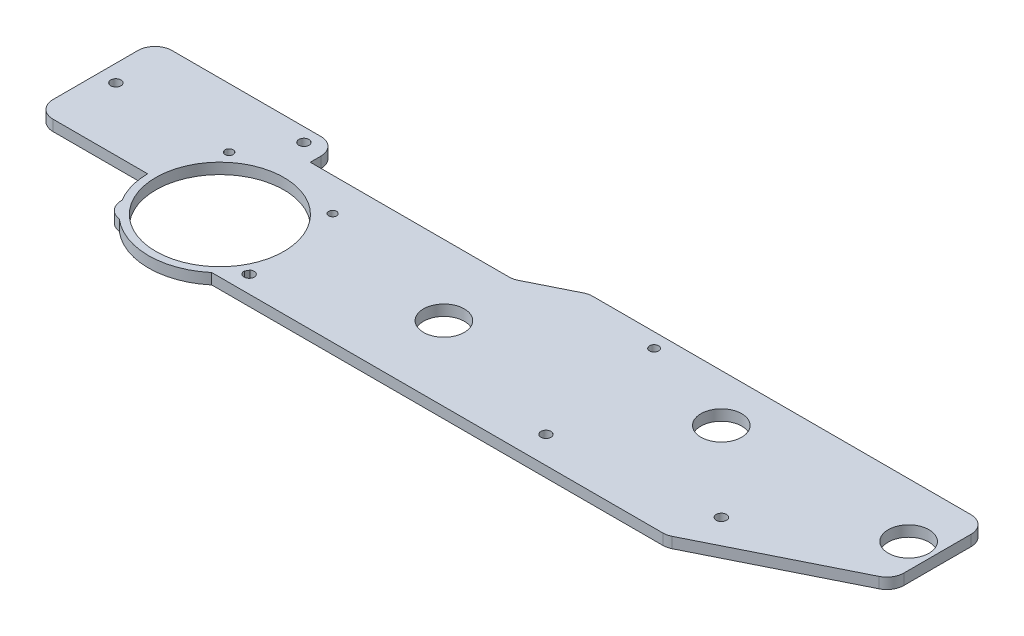
SolidWorks part; units mm, degrees
ref_plane "Front" through (0, 0, 0) normal (0, 0, 1) x (1, 0, 0)
ref_plane "Top" through (0, 0, 0) normal (0, 1, 0) x (1, 0, 0)
ref_plane "Right" through (0, 0, 0) normal (1, 0, 0) x (0, 0, -1)
sketch "Sketch1" plane through (0, 0, 0) normal (0, 1, 0) x (1, 0, 0)
  line L1 (0, 0) -> (210, 0)
  line L2 (0, 0) -> (0, -50)
  line L3 (0, -50) -> (210, -50)
  line L4 (210, 0) -> (210, -50)
  circle A7 centre (3.4895, -16.7877) radius 1.2117
  circle A8 centre (34.3726, -17.194) radius 1.1656
  circle A9 centre (37.5207, -44.9212) radius 1.5
  circle A12 centre (168.9752, -37.4032) radius 1.5173
  circle A13 centre (116, -4.2372) radius 1.3356
  circle A14 centre (12.2576, -3.2748) radius 1.6244
  dimension "D1" = 210
  dimension "D2" = 50
extrude "Boss-Extrude1" add sketch "Sketch1" along normal blind 3.175
sketch "Sketch2" plane through (0, 3.175, 0) normal (0, 1, 0) x (1, 0, 0)
  line L0 (210, 0) -> (0, 0) construction
  line L1 (0, 0) -> (0, -50) construction
  circle A0 centre (10, -26) radius 2
  circle A1 centre (10, -42) radius 2
  circle A2 centre (26, -26) radius 2
  circle A3 centre (26, -42) radius 2
  dimension "D1" = 16
  dimension "D2" = 16
  dimension "D3" = 16
  dimension "D4" = 26
  dimension "D5" = 10
  dimension "D6" = 10
  dimension "D7" = 26
  dimension "D8" = 16
extrude "Cut-Extrude1" cut sketch "Sketch2" against normal blind 10
sketch "Sketch3" plane through (0, 3.175, 0) normal (0, 1, 0) x (1, 0, 0)
  line L0 (210, 0) -> (0, 0) construction
  line L1 (210, 0) -> (0, 0) construction
  circle A0 centre (78.0103, -28.1) radius 6
  circle A1 centre (145.5313, -14) radius 6
  circle A2 centre (18, -34) radius 0.587
  circle A3 centre (26, -26) radius 2 construction
  circle A4 centre (202.6463, -16) radius 6
  dimension "D1" = 28.1
  dimension "D3" = 16
  dimension "D4" = 14
  dimension "D7" = 125.222
  dimension "D2" = 60.2996
  dimension "D5" = 8
  dimension "D6" = 8
  dimension "D8" = 57.15
extrude "Cut-Extrude2" cut sketch "Sketch3" against normal blind 57.15
sketch "Sketch4" [suppressed] plane through (0, 3.175, 0) normal (0, 1, 0) x (1, 0, 0)
  line L0 (3.4895, -16.7877) -> (18, -34)
  line L1 (3.4895, -20.6627) -> (5.9498, -23.5811)
  line L2 (18, -34) -> (34.3726, -17.194)
  line L3 (34.3726, -17.194) -> (75.8499, -28.1)
  line L4 (75.8499, -28.1) -> (37.5207, -44.9212)
  line L5 (7.3432, -17.194) -> (9.8664, -20.303)
  circle A0 centre (18, -34) radius 15.9299
  circle A1 centre (3.4895, -16.7877) radius 3.8751
  circle A2 centre (34.3726, -17.194) radius 3.7227
  circle A3 centre (37.5207, -44.9212) radius 3.8676
  circle A4 centre (75.8499, -28.1) radius 12.797
  circle A5 centre (112.3021, -4.7393) radius 5.1588
  circle A6 centre (118.879, -40.0177) radius 4.9035
  circle A7 centre (140.772, -16) radius 12.6375
  circle A8 centre (168.9752, -37.4032) radius 4.2066
  circle A9 centre (197.922, -16) radius 12.8
sketch "Sketch5" [suppressed] plane through (0, 3.175, 0) normal (0, 1, 0) x (1, 0, 0)
  line L0 (210, 0) -> (0, 0) construction
  line L2 (-0.6266, -16.7877) -> (37.5207, -16.7877)
  line L3 (-0.6266, -16.7877) -> (-0.6266, -44.9212)
  line L4 (-0.6266, -44.9212) -> (37.5207, -44.9212)
  line L5 (37.5207, -16.7877) -> (37.5207, -44.9212)
  line L6 (75.8499, -15.182) -> (37.5207, -15.182)
  line L7 (75.8499, -15.182) -> (75.8499, -44.9212)
  line L8 (75.8499, -44.9212) -> (37.5207, -44.9212)
  line L9 (37.5207, -15.182) -> (37.5207, -44.9212)
  line L10 (112.3021, -4.7393) -> (75.8499, -4.7393)
  line L11 (112.3021, -4.7393) -> (112.3021, -44.9212)
  line L12 (112.3021, -44.9212) -> (75.8499, -44.9212)
  line L13 (75.8499, -4.7393) -> (75.8499, -44.9212)
  line L14 (112.3021, -4.7393) -> (102.3945, -4.7393)
  line L16 (112.3021, -4.7393) -> (112.3021, 0)
  line L17 (112.3021, 0) -> (102.3945, 0)
  line L18 (102.3945, -4.7393) -> (102.3945, 0)
  line L19 (210, -50) -> (210, 0) construction
  line L20 (112.3021, -4.7393) -> (123.1553, -4.7393)
  line L21 (112.3021, -4.7393) -> (112.3021, 0)
  line L22 (112.3021, 0) -> (123.1553, 0)
  line L23 (123.1553, -4.7393) -> (123.1553, 0)
  line L24 (112.3021, -4.7393) -> (140.772, -4.7393)
  line L25 (112.3021, -4.7393) -> (112.3021, -40.0177)
  line L26 (112.3021, -40.0177) -> (140.772, -40.0177)
  line L27 (140.772, -4.7393) -> (140.772, -40.0177)
  line L28 (140.772, -16) -> (168.9752, -16)
  line L29 (140.772, -16) -> (140.772, -40.0177)
  line L30 (140.772, -40.0177) -> (168.9752, -40.0177)
  line L31 (168.9752, -16) -> (168.9752, -40.0177)
  line L32 (168.9752, -4.7393) -> (210, -4.7393)
  line L33 (168.9752, -4.7393) -> (168.9752, -40.0177)
  line L34 (168.9752, -40.0177) -> (210, -40.0177)
  line L35 (210, -4.7393) -> (210, -40.0177)
  line L36 (0, -50) -> (210, -50) construction
  line L37 (160.7629, -40.0177) -> (177.2091, -40.0177)
  line L38 (160.7629, -40.0177) -> (160.7629, -44.9212)
  line L39 (160.7629, -44.9212) -> (177.2091, -44.9212)
  line L40 (177.2091, -40.0177) -> (177.2091, -44.9212)
  line L41 (112.3021, -40.0177) -> (126.3591, -40.0177)
  line L42 (112.3021, -40.0177) -> (112.3021, -47.7828)
  line L43 (112.3021, -47.7828) -> (126.3591, -47.7828)
  line L44 (126.3591, -40.0177) -> (126.3591, -47.7828)
  line L45 (30.5963, -44.9212) -> (44.6115, -44.9212)
  line L46 (30.5963, -44.9212) -> (30.5963, -50)
  line L47 (30.5963, -50) -> (44.6115, -50)
  line L48 (44.6115, -44.9212) -> (44.6115, -50)
  line L50 (-0.6266, -44.9212) -> (30.5963, -44.9212)
  line L51 (-0.6266, -44.9212) -> (-0.6266, -50)
  line L52 (-0.6266, -50) -> (30.5963, -50)
  line L53 (30.5963, -44.9212) -> (30.5963, -50)
  circle A0 centre (3.4895, -16.7877) radius 4.1161
  circle A1 centre (34.3726, -17.194) radius 3.8132
  circle A2 centre (75.8499, -28.1) radius 12.918
  circle A3 centre (112.3021, -4.7393) radius 5.2663
  circle A4 centre (140.772, -16) radius 13.0245
  circle A5 centre (197.922, -16) radius 12.3805
  circle A6 centre (168.9752, -37.4032) radius 4.7643
  circle A7 centre (118.879, -40.0177) radius 5.279
  circle A8 centre (37.5207, -44.9212) radius 4.2049
  line M12 (0, 0) -> (0, -50)
  line M13 (0, -50) -> (210, -50)
  line M14 (210, -50) -> (210, 0)
  line M15 (210, 0) -> (0, 0)
extrude "Cut-Extrude5" [suppressed] cut sketch "Sketch5" against normal blind 11.52 contours A5 L32 L23 L24 A4 L28 L33 M14 M15 | A1 L6 L13 L10 L18 A0 L2 M15 M12 | L8 L48 L34 L40 L39 L38 L30 L26 L44 L43 L42 L12 M13 M14
fillet "Fillet1" [suppressed] radius 5
sketch "Sketch10" plane through (0, 3.175, 0) normal (0, 1, 0) x (1, 0, 0)
  line L0 (210, -27.8594) -> (165.5029, -50)
  line L1 (210, -50) -> (210, 0) construction
  line L2 (0, -50) -> (210, -50) construction
  line L3 (165.5029, -50) -> (210, -50)
  line L4 (210, -50) -> (210, -27.8594)
  line L5 (92.5326, 0) -> (77.6548, -7.4028)
  line L6 (210, 0) -> (0, 0) construction
  line L7 (77.6548, -7.4028) -> (0, -7.4028)
  line L8 (0, 0) -> (0, -50) construction
  line L9 (0, -7.4028) -> (0, 0)
  line L10 (0, 0) -> (92.5326, 0)
extrude "Cut-Extrude7" cut sketch "Sketch10" against normal blind 10
fillet "Fillet3" radius 5 7 edges at (0, 1.5875, 50) (0, 1.5875, 7.4028) (77.6548, 1.5875, 7.4028) (92.5326, 1.5875, 0) (210, 1.5875, 0) (210, 1.5875, 27.8594) (165.5029, 1.5875, 50)
sketch "Sketch11" plane through (0, 3.175, 0) normal (0, 1, 0) x (1, 0, 0)
  circle A0 centre (18, -34) radius 18.5
  circle A1 centre (10, -26) radius 2
  circle A2 centre (10, -42) radius 2
  circle A3 centre (26, -26) radius 2
  circle A4 centre (26, -42) radius 2
extrude "Boss-Extrude4" add sketch "Sketch11" against normal blind 3.175
sketch "Sketch12" plane through (0, 3.175, 0) normal (0, 1, 0) x (1, 0, 0)
  circle A0 centre (18, -34) radius 21
  circle A1 centre (10, -26) radius 2 construction
  circle A2 centre (10, -42) radius 2 construction
  dimension "D1" = 8
  dimension "D2" = 8
extrude "Boss-Extrude5" add sketch "Sketch12" against normal blind 3.175
sketch "Sketch13" plane through (0, 3.175, 0) normal (0, 1, 0) x (1, 0, 0)
  circle A0 centre (18, -34) radius 18.85
extrude "Cut-Extrude8" cut sketch "Sketch13" against normal blind 3.175
sketch "Sketch14" plane through (0, 3.175, 0) normal (0, 1, 0) x (1, 0, 0)
  line L0 (0, -12.4028) -> (0, -23.1833) construction
  line L1 (0, -34.2728) -> (-35.83, -34.2728)
  line L2 (0, -34.2728) -> (0, 0.7272)
  line L3 (0, 0.7272) -> (-35.83, 0.7272)
  line L4 (-35.83, -34.2728) -> (-35.83, 0.7272)
  line L5 (5, -7.4028) -> (76.4796, -7.4028) construction
  line L8 (0, 0.7272) -> (18, 0.7272)
  line L9 (0, 0.7272) -> (0, -12.2485)
  line L10 (0, -12.2485) -> (18, -12.2485)
  line L11 (18, 0.7272) -> (18, -12.2485)
  line M20 (76.4796, -7.4028) -> (5, -7.4028)
  arc M21 (5, -7.4028) -> (0, -12.4028) centre (5, -12.4028) ccw
  line M22 (0, -12.4028) -> (0, -23.1833)
  arc M23 (0, -23.1833) -> (0, -44.8167) centre (18, -34) ccw
  dimension "D4" = 18
  dimension "D1" = 8.13
  dimension "D2" = 35.83
  dimension "D3" = 35
extrude "Boss-Extrude6" add sketch "Sketch14" against normal blind 3.175 contours L4 L1 L2 L3 M23 M22 | L11 L8 L2 L10 M21 M20
fillet "Fillet4" radius 5 3 edges at (18, 1.5875, -0.7272) (-35.83, 1.5875, 34.2728) (-35.83, 1.5875, -0.7272)
sketch "Sketch15" plane through (0, 3.175, 0) normal (0, 1, 0) x (1, 0, 0)
  line L0 (210, -24.7625) -> (210, -5) construction
  circle A0 centre (122, -42.0581) radius 1.5
  dimension "D1" = 88
extrude "Cut-Extrude9" cut sketch "Sketch15" against normal blind 10
sketch "Sketch16" plane through (0, 3.175, 0) normal (0, 1, 0) x (1, 0, 0)
  line L0 (18, -4.2728) -> (18, -7.4028) construction
  line L1 (13, 0.7272) -> (-30.83, 0.7272) construction
  circle A0 centre (12, -3.2728) radius 1.5
  dimension "D1" = 6
  dimension "D2" = 4
extrude "Cut-Extrude10" cut sketch "Sketch16" against normal blind 10
sketch "Sketch17" plane through (0, 3.175, 0) normal (0, 1, 0) x (1, 0, 0)
  line L0 (13, 0.7272) -> (-30.83, 0.7272) construction
  line L1 (-35.83, -29.2728) -> (-35.83, -4.2728) construction
  circle A0 centre (-30.83, -15.7728) radius 1.5
  dimension "D1" = 16.5
  dimension "D2" = 5
extrude "Cut-Extrude11" cut sketch "Sketch17" against normal blind 10
